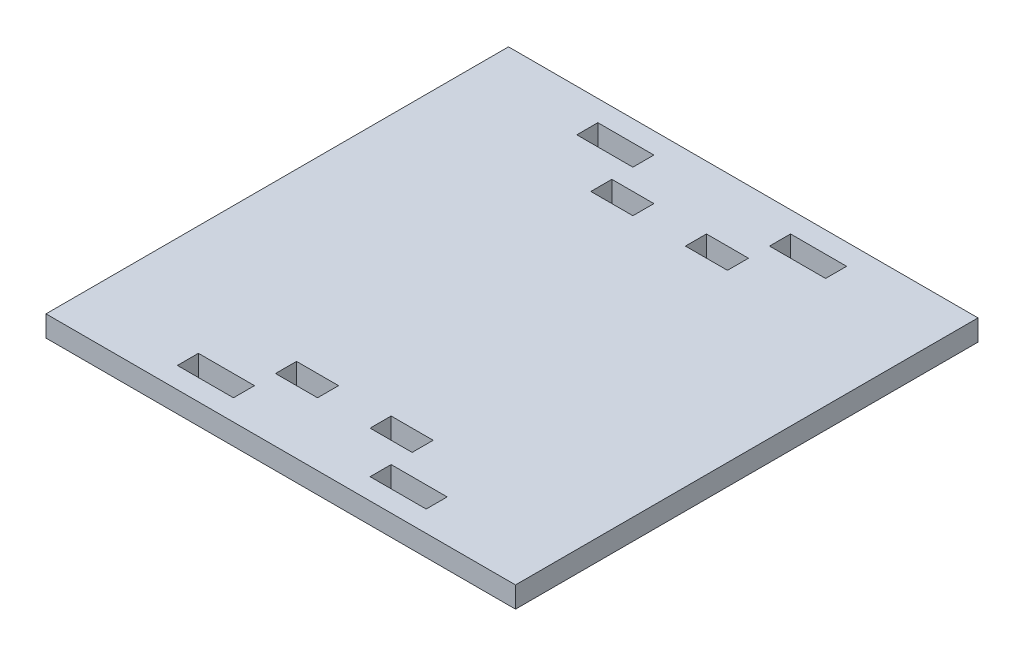
SolidWorks part; units mm, degrees
ref_plane "Plano frontal" through (0, 0, 0) normal (0, 0, 1) x (1, 0, 0)
ref_plane "Plano superior" through (0, 0, 0) normal (0, 1, 0) x (1, 0, 0)
ref_plane "Plano direito" through (0, 0, 0) normal (1, 0, 0) x (0, 0, -1)
sketch "Esboço1" plane through (0, 0, 0) normal (0, 1, 0) x (1, 0, 0)
  line L1 (9.75, -27) -> (9.75, -28.5)
  line L2 (-33.5, -27.5) -> (-33.5, 28)
  line L3 (-9.75, 27) -> (-16.9293, 27)
  line L4 (33.5, -27.5) -> (33.5, 28)
  line L11 (-9.75, 33) -> (-33.5, 33)
  line L12 (-33.5, 33) -> (-33.5, 28)
  line L13 (-9.75, 33) -> (33.5, 33)
  line L19 (33.5, 33) -> (33.5, 28)
  line L20 (-3.75, 24) -> (-3.75, 21)
  line L21 (-3.75, 21) -> (-9.75, 21)
  line L22 (-9.75, 21) -> (-9.75, 24)
  line L23 (-9.75, 24) -> (-3.75, 24)
  line L24 (-9.75, 28.5) -> (-9.75, 30)
  line L25 (9.75, 24) -> (9.75, 21)
  line L26 (9.75, 21) -> (3.75, 21)
  line L27 (3.75, 21) -> (3.75, 24)
  line L28 (3.75, 24) -> (9.75, 24)
  line L29 (17.75, -27) -> (9.75, -27)
  line L30 (17.75, -30) -> (17.75, -27)
  line L31 (9.75, -30) -> (17.75, -30)
  line L32 (9.75, -28.5) -> (9.75, -30)
  line L33 (-9.75, -27) -> (-9.75, -28.5)
  line L34 (-9.75, 30) -> (-17.75, 30)
  line L35 (-17.75, -27) -> (-9.75, -27)
  line L36 (-17.75, -30) -> (-17.75, -27)
  line L37 (-9.75, -30) -> (-17.75, -30)
  line L38 (3.75, -24) -> (9.75, -24)
  line L39 (-17.75, 30) -> (-17.75, 27)
  line L40 (3.75, -21) -> (3.75, -24)
  line L41 (9.75, -21) -> (3.75, -21)
  line L42 (9.75, -24) -> (9.75, -21)
  line L43 (-9.75, -28.5) -> (-9.75, -30)
  line L44 (-17.75, 27) -> (-9.75, 27)
  line L45 (-9.75, 27) -> (-9.75, 28.5)
  line L46 (9.75, 28.5) -> (9.75, 30)
  line L47 (9.75, 30) -> (17.75, 30)
  line L48 (17.75, 30) -> (17.75, 27)
  line L49 (17.75, 27) -> (9.75, 27)
  line L50 (9.75, 27) -> (9.75, 28.5)
  line L51 (-9.75, -24) -> (-3.75, -24)
  line L52 (-9.75, -21) -> (-9.75, -24)
  line L53 (-3.75, -21) -> (-9.75, -21)
  line L54 (-3.75, -24) -> (-3.75, -21)
  line L55 (33.5, -33) -> (33.5, -28)
  line L61 (-9.75, -33) -> (33.5, -33)
  line L62 (-33.5, -33) -> (-33.5, -28)
  line L63 (-9.75, -33) -> (-33.5, -33)
  line L64 (-9.75, -27) -> (-16.9293, -27)
  line L65 (-33.5, -27.5) -> (-33.5, -28)
  line L66 (33.5, -27.5) -> (33.5, -28)
extrude "Ressalto-extrusão1" add sketch "Esboço1" along normal blind 3
